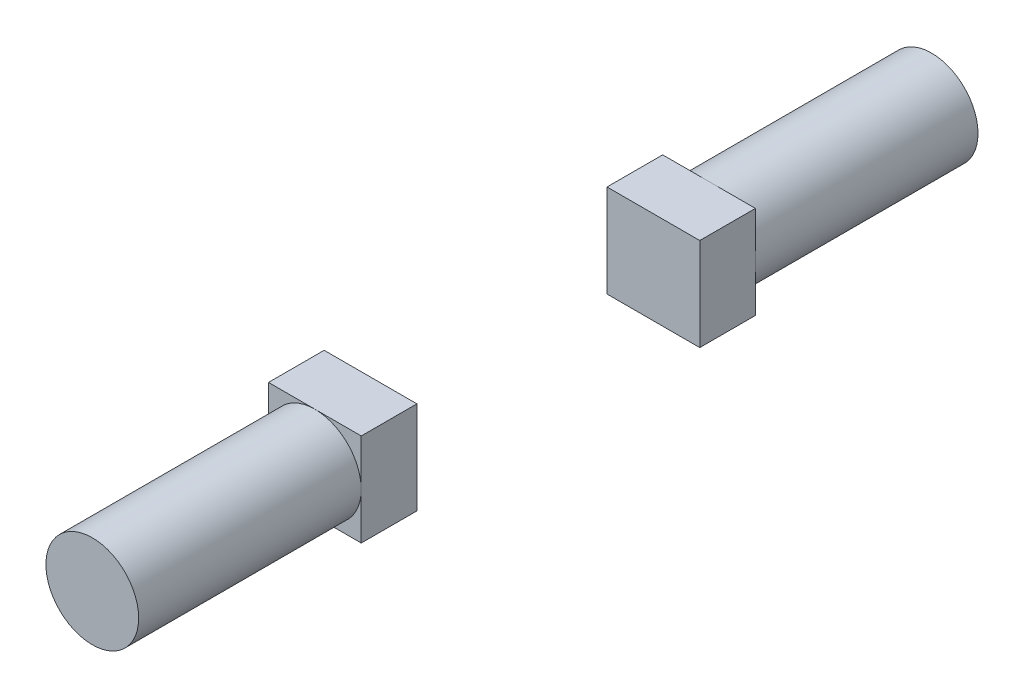
SolidWorks part; units mm, degrees
ref_plane "Front Plane" through (0, 0, 0) normal (0, 0, 1) x (1, 0, 0)
ref_plane "Top Plane" through (0, 0, 0) normal (0, 1, 0) x (1, 0, 0)
ref_plane "Right Plane" through (0, 0, 0) normal (1, 0, 0) x (0, 0, -1)
sketch "Sketch1" plane through (0, 0, 0) normal (0, 0, 1) x (1, 0, 0)
  line L5 (-5.08, 5.08) -> (5.08, 5.08)
  line L6 (-5.08, 5.08) -> (-5.08, -5.08)
  line L7 (-5.08, -5.08) -> (5.08, -5.08)
  line L8 (5.08, 5.08) -> (5.08, -5.08)
  line L9 (-5.08, 5.08) -> (5.08, -5.08) construction
  line L10 (-5.08, -5.08) -> (5.08, 5.08) construction
  point P0 (0, 0)
  dimension "D1" = 10.16
  dimension "D2" = 10.16
extrude "Boss-Extrude2" add sketch "Sketch1" along normal mid plane 43.18
sketch "Sketch2" plane through (0, 0, 21.59) normal (0, 0, 1) x (1, 0, 0)
  circle A0 centre (0, 0) radius 5.08
  dimension "D1" = 10.16
extrude "Boss-Extrude3" add sketch "Sketch2" along normal blind 24.384
mirror "Mirror1" about plane through (0, 0, 0) normal (0, 0, 1) of "Boss-Extrude3"
sketch "Sketch4" plane through (5.08, 0, 0) normal (1, 0, 0) x (0, 0, -1)
  line L0 (-21.59, -5.08) -> (21.59, -5.08) construction
  line L1 (-15.494, 5.08) -> (15.494, 5.08)
  line L2 (-15.494, 5.08) -> (-15.494, -5.08)
  line L3 (-15.494, -5.08) -> (15.494, -5.08)
  line L4 (15.494, 5.08) -> (15.494, -5.08)
  line L5 (-15.494, 5.08) -> (15.494, -5.08) construction
  line L6 (-15.494, -5.08) -> (15.494, 5.08) construction
  line L7 (-21.59, 0) -> (-21.59, 5.08) construction
  point P0 (0, 0)
  point P8 (13.9377, 5.08)
  dimension "D1" = 6.096
extrude "Cut-Extrude2" cut sketch "Sketch4" against normal through all
